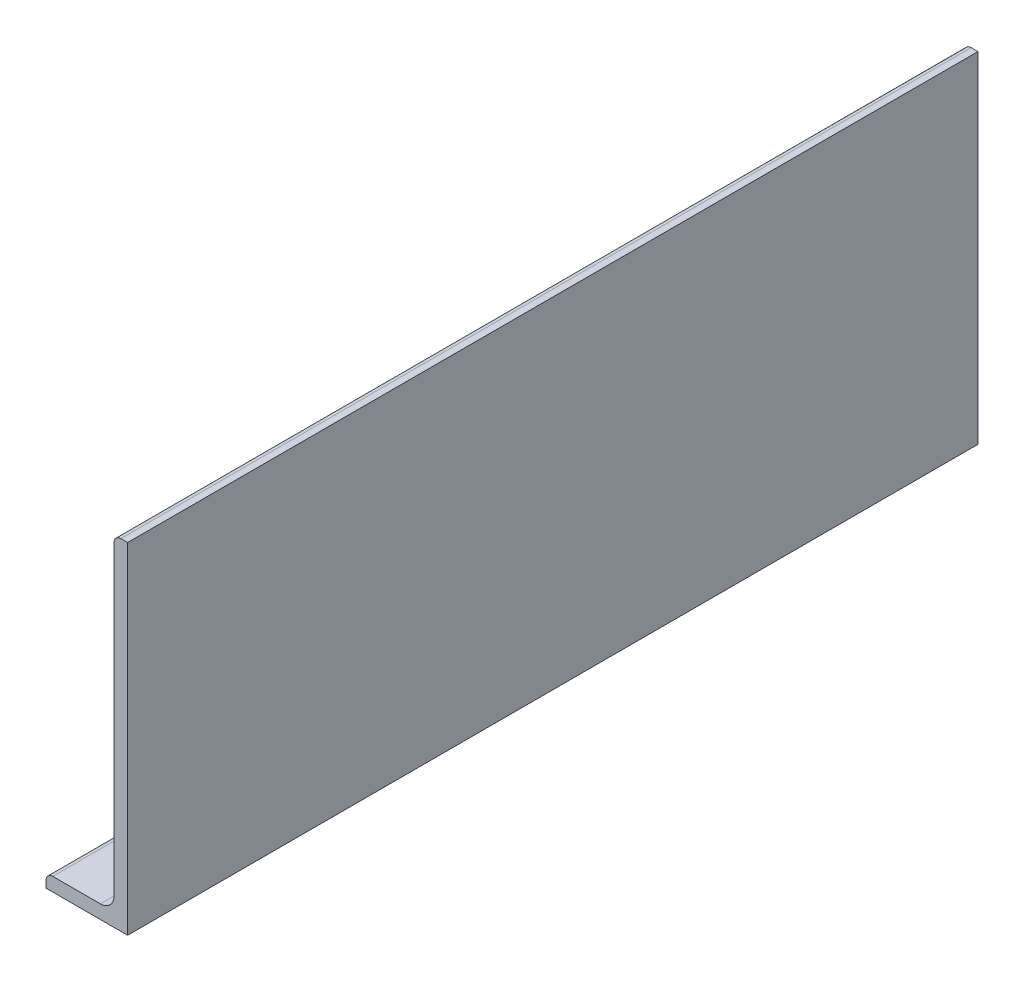
SolidWorks part; units mm, degrees
ref_plane "Front Plane" through (0, 0, 0) normal (0, 0, 1) x (1, 0, 0)
ref_plane "Top Plane" through (0, 0, 0) normal (0, 1, 0) x (1, 0, 0)
ref_plane "Right Plane" through (0, 0, 0) normal (1, 0, 0) x (0, 0, -1)
sketch "Sketch1" plane through (0, 0, 0) normal (0, 0, 1) x (1, 0, 0)
  line L0 (326.672, -19.4192) -> (326.672, -69.4192)
  line L1 (326.672, -69.4192) -> (314.672, -69.4192)
  line L2 (314.672, -69.4192) -> (314.672, -67.4192)
  line L3 (314.672, -67.4192) -> (324.672, -67.4192)
  line L4 (324.672, -67.4192) -> (324.672, -19.4192)
  line L5 (324.672, -19.4192) -> (326.672, -19.4192)
  dimension "D1" = 2
  dimension "D2" = 2
  dimension "D3" = 50
  dimension "D4" = 12
extrude "Boss-Extrude1" add sketch "Sketch1" along normal blind 125
fillet "Fillet1" radius 1 2 edges at (314.672, -67.4192, 62.5) (324.672, -19.4192, 62.5)
fillet "Fillet2" radius 2 1 edges at (324.672, -67.4192, 62.5)
sketch "Sketch2" plane through (0, -67.4192, 0) normal (0, 1, 0) x (1, 0, 0)
  line L0 (314.672, -125) -> (314.672, 0) construction
  line L1 (322.672, 0) -> (315.672, 0) construction
  line L2 (322.672, -125) -> (315.672, -125) construction
  circle A0 centre (319.172, -105) radius 1.6
  circle A1 centre (319.172, -20) radius 1.6
  dimension "D1" = 3.2
  dimension "D2" = 3.2
  dimension "D3" = 4.5
  dimension "D4" = 4.5
  dimension "D5" = 20
  dimension "D6" = 20
extrude "Cut-Extrude1" cut sketch "Sketch2" against normal through all
